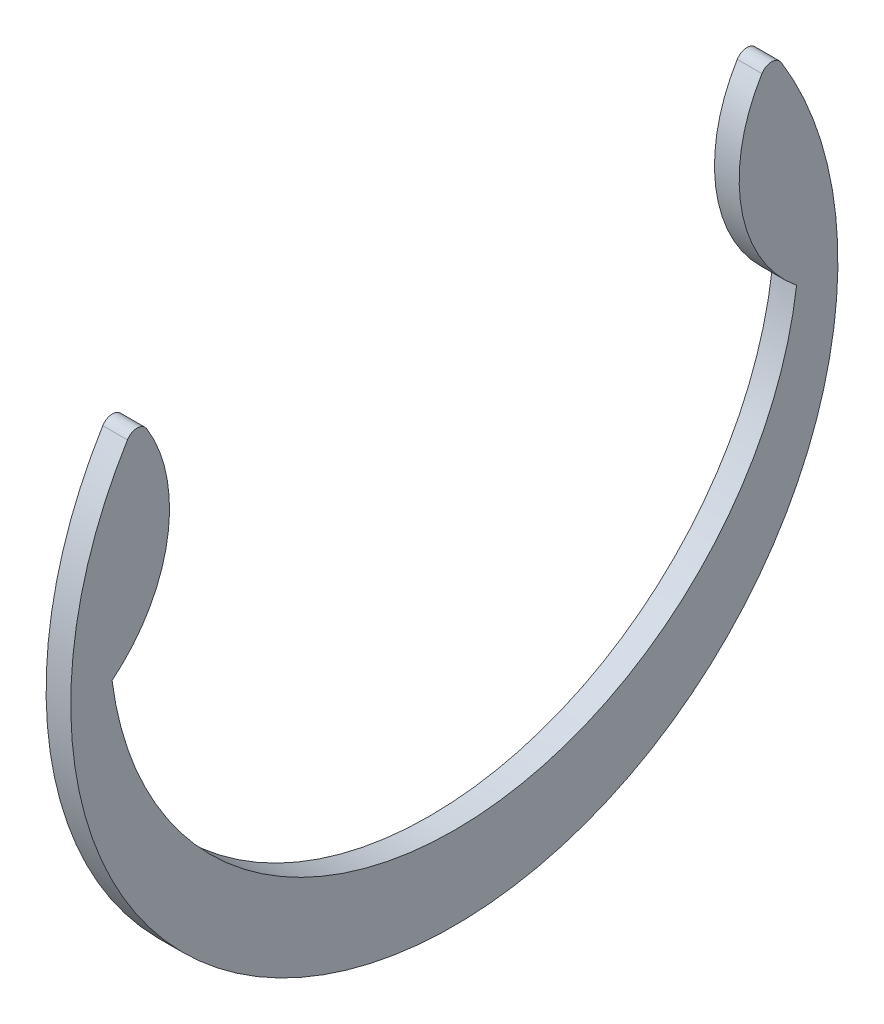
SolidWorks part; units mm, degrees
material "Steel Spring  ASTM A228 "
ref_plane "Front" through (0, 0, 0) normal (0, 0, 1) x (1, 0, 0)
ref_plane "Top" through (0, 0, 0) normal (0, 1, 0) x (1, 0, 0)
ref_plane "Right" through (0, 0, 0) normal (1, 0, 0) x (0, 0, -1)
sketch "Sketch1" plane through (0, 0, 0) normal (1, 0, 0) x (0, 0, -1)
  circle A0 centre (0, 0) radius 15.494 construction
  arc A1 (-17.6212, 0) -> (17.6212, 0) centre (0, 2.2733) ccw
  circle A2 centre (0, 0) radius 19.7485 construction
  circle A3 centre (0, 0) radius 20.066 construction
  arc A4 (16.8318, 10.3293) -> (-16.8318, 10.3293) centre (0, 0) cw
  arc A5 (-15.8359, 10.3293) -> (-17.6212, 0) centre (-22.6, 6.1794) cw
  arc A6 (-16.8318, 10.3293) -> (-15.8359, 10.3293) centre (-16.3339, 10.0238) cw
  arc A7 (16.8318, 10.3293) -> (15.8359, 10.3293) centre (16.3339, 10.0238) ccw
  arc A8 (17.6212, 0) -> (15.8359, 10.3293) centre (22.6, 6.1794) cw
  arc A9 (15.8359, 10.3293) -> (17.6212, 0) centre (0, 2.2733) cw construction
  dimension "A" = 30.988
  dimension "OD" = 39.497
  dimension "D1" = 10.3293
  dimension "D2" = 35.2425
extrude "Extrude1" add sketch "Sketch1" along normal mid plane 1.27
sketch "Sketch2" plane through (0, 0, 0) normal (0, 0, 1) x (1, 0, 0)
  line L0 (-3.556, 0) -> (10.668, 0)
  line L1 (10.668, 0) -> (10.668, -17.4625)
  line L3 (10.668, -17.4625) -> (0.7112, -17.4625)
  line L4 (0.7112, -17.4625) -> (0.7112, -15.7099)
  line L5 (0.7112, -15.7099) -> (-0.7112, -15.7099)
  line L6 (-0.7112, -15.7099) -> (-0.7112, -17.4625)
  line L7 (-0.7112, -17.4625) -> (-3.556, -17.4625) construction
  line L8 (-3.556, -17.4625) -> (-3.556, 0) construction
  line L9 (0, -15.7099) -> (0, 0) construction
  line L10 (10.668, 0) -> (14.0551, 0) construction
  line L11 (-0.7112, -17.4625) -> (-2.6797, -17.4625)
  line L12 (-2.6797, -17.4625) -> (-3.556, -16.5862)
  line L13 (-3.556, -16.5862) -> (-3.556, 0)
  point P14 (-0.7112, -16.5862)
  dimension "D2" = 14.224
  dimension "D3" = 3.556
  dimension "D4" = 45
revolve "Revolve1" [suppressed] add sketch "Sketch2" angle 360 about L10
equation "\"D2@Sketch2\" = \"W@Sketch2\"*10"
equation "\"D3@Sketch2\" = \"D2@Sketch2\"/4"
equation "\"D1@Sketch1\" = \"A@Sketch1\"/3"
equation "\"D2@Sketch1\" = (\"OD@Sketch1\"+\"A@Sketch1\")/2"
